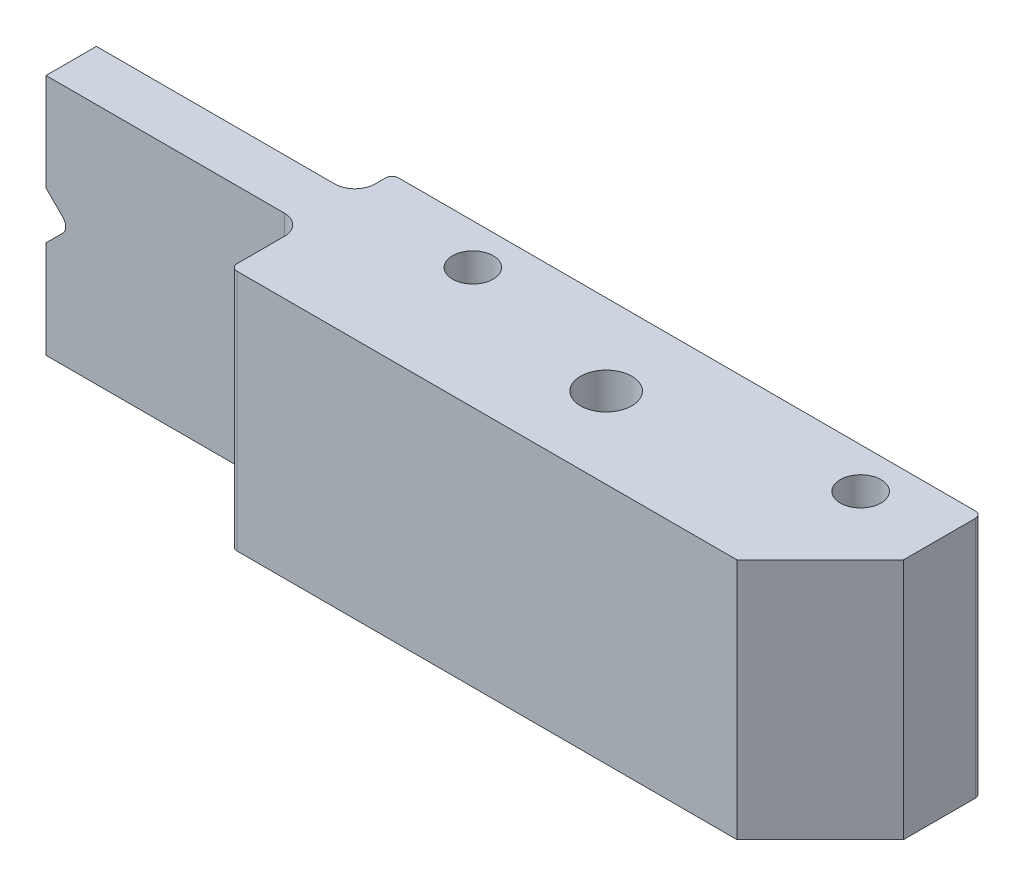
SolidWorks part; units mm, degrees
material "Acero M2"
ref_plane "Alzado" through (0, 0, 0) normal (0, 0, 1) x (1, 0, 0)
ref_plane "Planta" through (0, 0, 0) normal (0, 1, 0) x (1, 0, 0)
ref_plane "Vista lateral" through (0, 0, 0) normal (1, 0, 0) x (0, 0, -1)
sketch "Croquis1" plane through (0, 0, 0) normal (0, 0, 1) x (1, 0, 0)
  line L1 (0, 0) -> (66.675, 0)
  line L2 (0, 0) -> (0, -19.05)
  line L3 (0, -19.05) -> (66.675, -19.05)
  line L4 (66.675, 0) -> (66.675, -19.05)
  line L5 (33.3375, -19.05) -> (33.3375, 0) construction
  line L6 (0, -9.525) -> (66.675, -9.525) construction
  point P188 (33.3375, -9.525)
  dimension "D1" = 66.675
  dimension "D2" = 19.05
extrude "Saliente-Extruir1" add sketch "Croquis1" along normal blind 12.7
sketch "Croquis2" plane through (0, 0, 0) normal (0, 1, 0) x (1, 0, 0)
  line L1 (0, 0) -> (20.32, 0)
  line L2 (0, 0) -> (0, -2.921)
  line L3 (0, -2.921) -> (20.32, -2.921)
  line L4 (20.32, 0) -> (20.32, -2.921)
  line L5 (10.16, -2.921) -> (10.16, 0) construction
  line L6 (0, -1.4605) -> (20.32, -1.4605) construction
  line L7 (0, -12.7) -> (20.32, -12.7)
  line L8 (0, -12.7) -> (0, -6.8834)
  line L9 (0, -6.8834) -> (20.32, -6.8834)
  line L10 (20.32, -12.7) -> (20.32, -6.8834)
  line L11 (10.16, -6.8834) -> (10.16, -12.7) construction
  line L12 (0, -9.7917) -> (20.32, -9.7917) construction
  point P144 (10.16, -1.4605)
  point P182 (10.16, -9.7917)
  dimension "D1" = 20.32
  dimension "D2" = 2.921
  dimension "D3" = 3.9624
extrude "Cortar-Extruir1" cut sketch "Croquis2" against normal through all
fillet "Redondeo1" radius 1.5875 2 edges at (20.32, -9.525, 2.921) (20.32, -9.525, 6.8834)
hole_wizard "Taladros de espiga de 1/8 (0.126)1" positions "Croquis3" profile "Croquis4" hole size "1/8" standard "Ansi Inch" end condition through all
sketch "Croquis3" plane through (0, 0, 0) normal (0, 1, 0) x (1, 0, 0)
  line L0 (29.845, -3.175) -> (60.325, -3.175) construction
  line L2 (66.675, 0) -> (20.32, 0) construction
  line L3 (66.675, -12.7) -> (66.675, 0) construction
  point P0 (60.325, -3.175)
  point P2 (29.845, -3.175)
  dimension "D1" = 3.175
  dimension "D2" = 6.35
  dimension "D3" = 36.83
sketch "Croquis4" plane through (60.325, 0, 3.175) normal (1, 0, 0) x (0, 0, 1)
  line L0 (0, 0) -> (0, 19.05)
  line L1 (0, 19.05) -> (1.6002, 19.05)
  line L2 (1.6002, 19.05) -> (1.6002, 0)
  line L5 (1.6002, 0) -> (0, 0)
  line L11 (0, -6.35) -> (0, 107.95) construction
  dimension "Diámetro de taladro hasta el siguiente" = 3.2004
  dimension "Profundidad de taladro hasta el siguiente" = 19.05
hole_wizard "Taladro roscado #10-321" positions "Croquis5" profile "Croquis6" tap size "#10-32" standard "Ansi Inch" end condition through all
sketch "Croquis5" plane through (0, 0, 0) normal (0, 1, 0) x (1, 0, 0)
  line L0 (66.675, -12.7) -> (66.675, 0) construction
  line L1 (66.675, 0) -> (20.32, 0) construction
  point P0 (43.4975, -6.35)
  dimension "D1" = 23.1775
  dimension "D2" = 6.35
sketch "Croquis6" plane through (43.4975, 0, 6.35) normal (1, 0, 0) x (0, 0, 1)
  line L0 (0, 0) -> (0, 19.05)
  line L1 (0, 19.05) -> (2.0193, 19.05)
  line L2 (2.0193, 19.05) -> (2.0193, 0)
  line L5 (2.0193, 0) -> (0, 0)
  line L11 (0, -6.35) -> (0, 107.95) construction
  dimension "Diámetro de perforador para roscar hasta el siguiente" = 4.0386
  dimension "Profundidad de perforador para roscar hasta el siguiente" = 19.05
cosmetic thread "Rosca de taladro1" parameters "D2"=4.826
sketch "Croquis7" plane through (0, 0, 0) normal (0, 1, 0) x (1, 0, 0)
  line L0 (66.675, -6.1468) -> (60.1218, -12.7)
  line L1 (66.675, -12.7) -> (66.675, 0) construction
  line L2 (66.675, -12.7) -> (20.32, -12.7) construction
  line L3 (60.1218, -12.7) -> (66.675, -12.7)
  line L4 (66.675, -12.7) -> (66.675, -6.1468)
  dimension "D1" = 45
  dimension "D2" = 6.1468
extrude "Cortar-Extruir2" cut sketch "Croquis7" against normal through all
sketch "Croquis8" plane through (0, 0, 2.921) normal (0, 0, -1) x (-1, 0, 0)
  line L0 (0, -7.66) -> (-1.3262, -8.9862)
  line L1 (0, -19.05) -> (0, 0) construction
  line L2 (-1.3262, -10.0638) -> (0, -11.39)
  line L3 (0, -11.39) -> (0, -7.66)
  line L4 (-0.7874, -9.525) -> (0, -9.525) construction
  arc A0 (-1.3262, -10.0638) -> (-1.3262, -8.9862) centre (-0.7874, -9.525) cw
  point P10 (-1.5494, -9.525)
  point P18 (0, -9.525)
  dimension "D1" = 0.762
  dimension "D2" = 1.5494
  dimension "D3" = 90
extrude "Cortar-Extruir3" cut sketch "Croquis8" against normal through all
sketch "Croquis10" plane through (0, 0, 0) normal (0, 0, -1) x (-1, 0, 0)
  line L0 (-61.7021, -12.7) -> (-25.2929, -12.7) construction
  line L1 (-43.4975, -12.7) -> (-43.4975, -19.05) construction
  line L2 (-20.32, -19.05) -> (-66.675, -19.05) construction
  text T0 "MM 90-4150-06"
  dimension "D1" = 6.35
extrude "Cortar-Extruir4" cut sketch "Croquis10" against normal blind 0.381
fillet "Redondeo2" radius 0.508 3 edges at (66.675, -9.525, 0) (20.32, -9.525, 12.7) (20.32, -9.525, 0)
